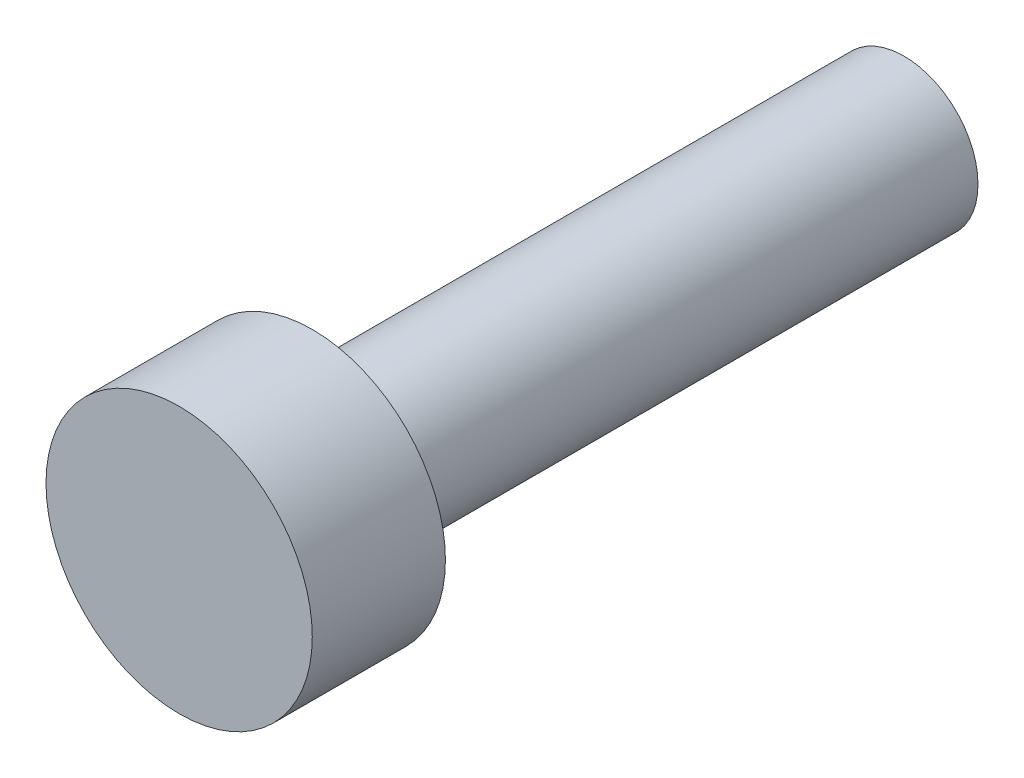
SolidWorks part; units mm, degrees
ref_plane "Front Plane" through (0, 0, 0) normal (0, 0, 1) x (1, 0, 0)
ref_plane "Top Plane" through (0, 0, 0) normal (0, 1, 0) x (1, 0, 0)
ref_plane "Right Plane" through (0, 0, 0) normal (1, 0, 0) x (0, 0, -1)
sketch "Sketch1" plane through (0, 0, 0) normal (0, 0, 1) x (1, 0, 0)
  circle A0 centre (0, 0) radius 1
  dimension "D1" = 2
extrude "Boss-Extrude1" add sketch "Sketch1" along normal blind 8
sketch "Sketch2" plane through (0, 0, 8) normal (0, 0, 1) x (1, 0, 0)
  circle A0 centre (0, 0) radius 1.8
  dimension "D1" = 3.6
extrude "Boss-Extrude2" add sketch "Sketch2" along normal blind 1.8
